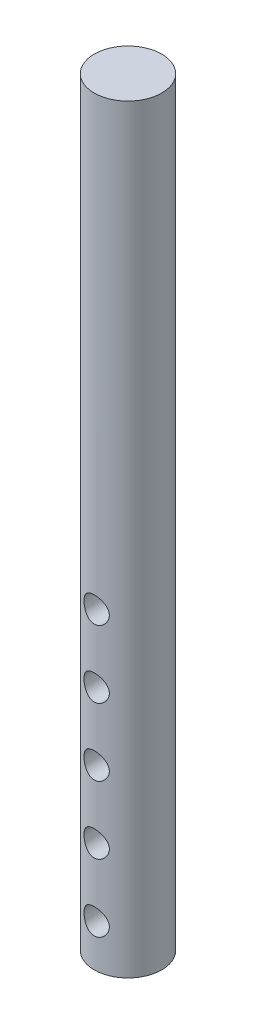
SolidWorks part; units mm, degrees
ref_plane "Front Plane" through (0, 0, 0) normal (0, 0, 1) x (1, 0, 0)
ref_plane "Top Plane" through (0, 0, 0) normal (0, 1, 0) x (1, 0, 0)
ref_plane "Right Plane" through (0, 0, 0) normal (1, 0, 0) x (0, 0, -1)
sketch "Sketch1" plane through (0, 0, 0) normal (0, 1, 0) x (1, 0, 0)
  circle A0 centre (0, 0) radius 2.54
  dimension "D1" = 5.08
extrude "Boss-Extrude1" add sketch "Sketch1" along normal blind 57.15
ref_plane "Plane1" through (0, 0, 2.54) normal (0, 0, 1) x (1, 0, 0)
sketch "Sketch2" plane through (0, 0, 2.54) normal (0, 0, 1) x (1, 0, 0)
  line L0 (0, 57.15) -> (0, 0) construction
  line L1 (2.54, 57.15) -> (-2.54, 57.15) construction
  circle A0 centre (0, 18.415) radius 0.9525
  circle A1 centre (0, 13.335) radius 0.9525
  circle A2 centre (0, 8.255) radius 0.9525
  circle A3 centre (0, 23.495) radius 0.9525
  circle A4 centre (0, 3.175) radius 0.9525
  dimension "D1" = 1.905
  dimension "D6" = 5.08
  dimension "D2" = 8.255
  dimension "D3" = 5.08
  dimension "D4" = 5.08
  dimension "D5" = 5.08
extrude "Cut-Extrude1" cut sketch "Sketch2" against normal blind 1.905
scale "Scale1" bodies to scale 102 scale about centroid uniform scaling yes scale factor 1.5
